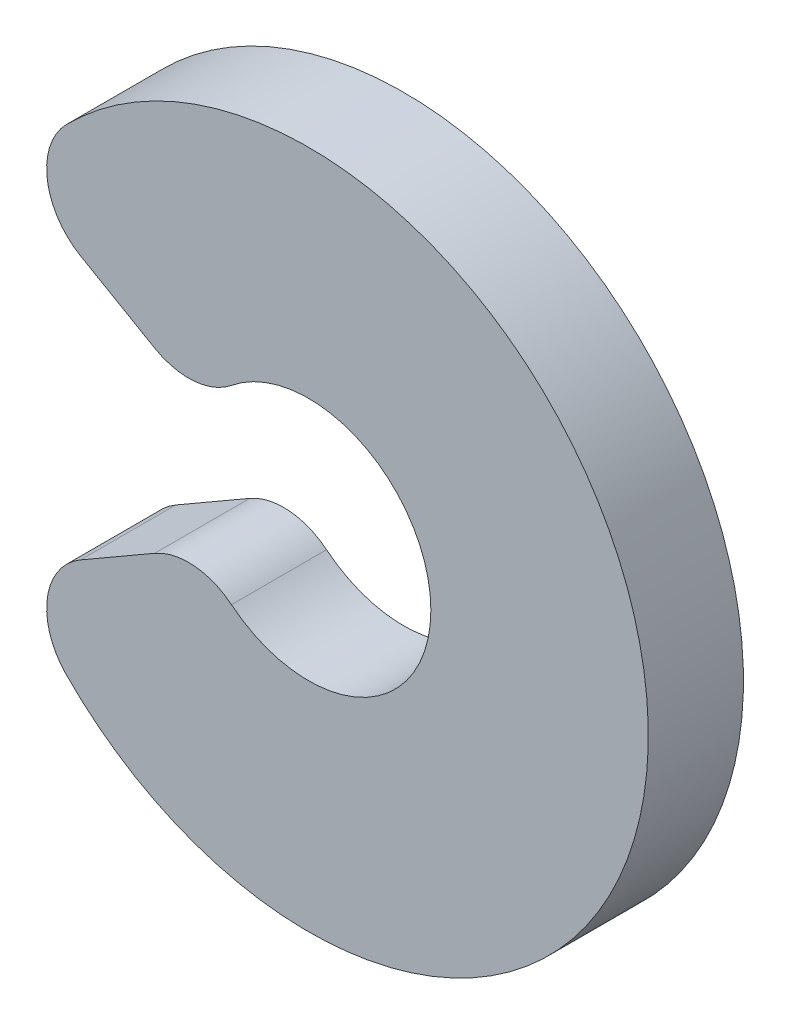
SolidWorks part; units mm, degrees
ref_plane "Plan de face" through (0, 0, 0) normal (1, 0, 0) x (0, 1, 0)
ref_plane "Plan de dessus" through (0, 0, 0) normal (0, 0, 1) x (0, 1, 0)
ref_plane "Plan de droite" through (0, 0, 0) normal (0, 1, 0) x (-1, 0, 0)
sketch "Esquisse1" plane through (0, 0, 0) normal (0, 0, 1) x (0, 1, 0)
  line L0 (0, 0) -> (-2.5, 4.3301)
  line L1 (0, 0) -> (2.5, 4.3301)
  line L2 (0, 0) -> (0, 9.4656) construction
  circle A0 centre (0, 0) radius 1.8
  circle A1 centre (0, 0) radius 5
  dimension "D1" = 10
  dimension "D2" = 3.6
  dimension "D3" = 30
extrude "Boss.-Extru.1" add sketch "Esquisse1" along normal blind 1.4 contours L0 A1 L1 A0
fillet "Congé1" radius 1 4 edges at (-4.3301, 2.5, 0.7) (-4.3301, -2.5, 0.7) (-1.5588, 0.9, 0.7) (-1.5588, -0.9, 0.7)
